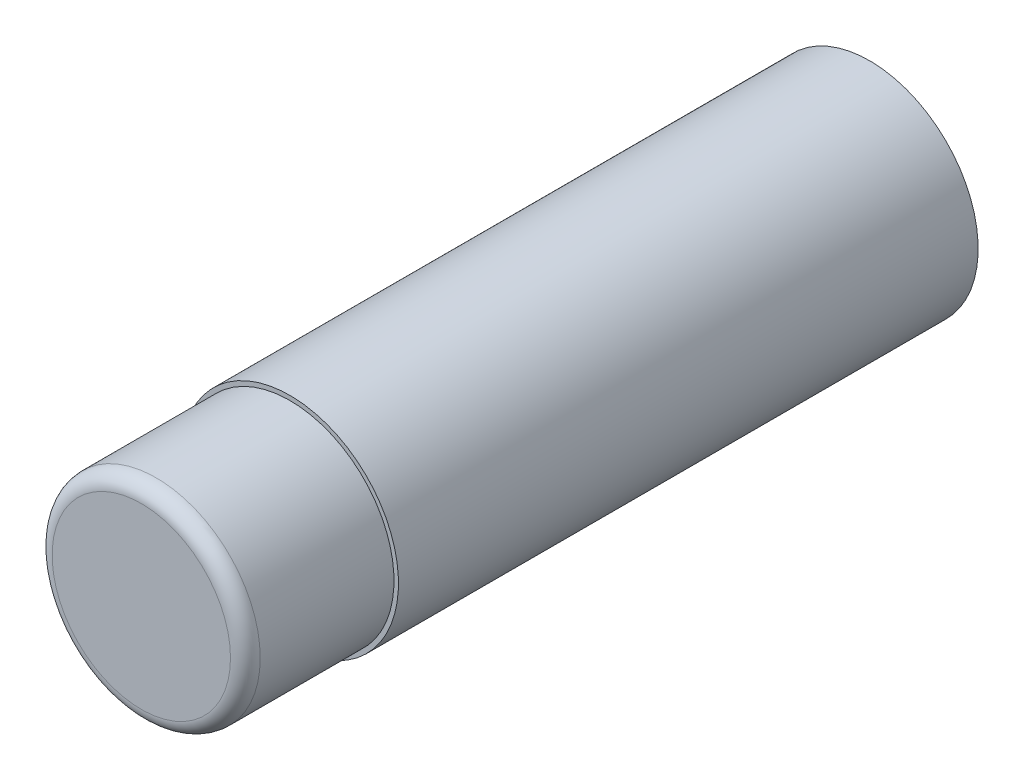
SolidWorks part; units mm, degrees
ref_plane "Ebene vorne" through (0, 0, 0) normal (0, 0, 1) x (1, 0, 0)
ref_plane "Ebene oben" through (0, 0, 0) normal (0, 1, 0) x (1, 0, 0)
ref_plane "Ebene rechts" through (0, 0, 0) normal (1, 0, 0) x (0, 0, -1)
sketch "Skizze1" plane through (0, 0, 0) normal (0, 0, 1) x (1, 0, 0)
  circle A0 centre (0, 0) radius 3.5
  dimension "D1" = 7
extrude "Aufsatz-Linear austragen1" add sketch "Skizze1" along normal blind 24.5 contours A0
fillet "Verrundung1" radius 0.5 1 edges at (3.5, 0, 24.5)
sketch "Skizze2" plane through (0, 0, 0) normal (0, 0, -1) x (-1, 0, 0)
  circle A0 centre (0, 0) radius 3.65
  dimension "D1" = 7.3
extrude "Aufsatz-Linear austragen2" add sketch "Skizze2" against normal blind 19.5 contours A0
